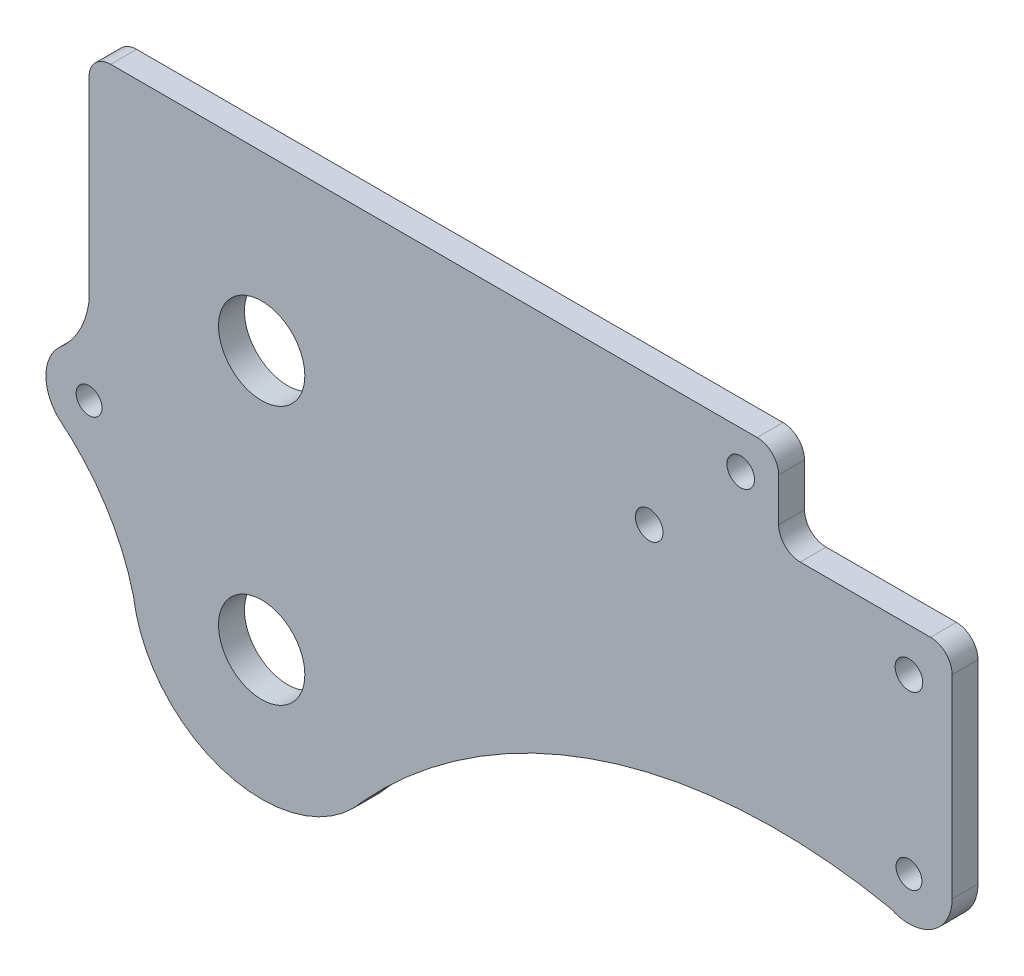
SolidWorks part; units mm, degrees
material "ｱｸﾘﾙ (中-上級の耐衝撃性)"
ref_plane "正面" through (0, 0, 0) normal (0, 0, 1) x (1, 0, 0)
ref_plane "平面" through (0, 0, 0) normal (0, 1, 0) x (1, 0, 0)
ref_plane "右側面" through (0, 0, 0) normal (1, 0, 0) x (0, 0, -1)
sketch "ｽｹｯﾁ1" plane through (0, 0, 0) normal (0, 0, 1) x (1, 0, 0)
  line L0 (0, 50) -> (100, 50) construction
  line L3 (0, 60) -> (100, 60)
  line L4 (100, 50) -> (100, 60)
  line L5 (10, 60) -> (50, 60)
  line L6 (10, 60) -> (10, 40)
  line L7 (10, 40) -> (50, 40)
  line L8 (50, 60) -> (50, 40)
  line L9 (30, 60) -> (30, 40) construction
  line L10 (100, 50) -> (100, 0)
  line L13 (0, 0) -> (100, 0)
  line L14 (0, 60) -> (0, 0)
  line L15 (20, 50) -> (20, 0) construction
  circle A0 centre (5.25, 55) radius 2.15
  circle A1 centre (5.25, 45) radius 2.15
  circle A2 centre (54.75, 55) radius 2.15
  circle A3 centre (54.75, 45) radius 2.15
  circle A4 centre (20, 20) radius 5
  dimension "D4" = 4.3
  dimension "D5" = 4.75
  dimension "D6" = 5
  dimension "D10" = 10
  dimension "D12" = 30
  dimension "D1" = 10
  dimension "D2" = 20
  dimension "D3" = 30
  dimension "D7" = 60
  dimension "D8" = 40
  dimension "D9" = 100
  dimension "D11" = 10
extrude "ﾎﾞｽ - 押し出し1" add sketch "ｽｹｯﾁ1" along normal blind 3
sketch "ｽｹｯﾁ2" plane through (0, 0, 3) normal (0, 0, 1) x (1, 0, 0)
  line L1 (100, 60) -> (100, 0) construction
  line L2 (50, 60) -> (100, 60) construction
  circle A1 centre (95, 35) radius 1.5
  dimension "D1" = 3
  dimension "D4" = 5
  dimension "D5" = 25
extrude "ｶｯﾄ - 押し出し1" cut sketch "ｽｹｯﾁ2" against normal through all
sketch "ｽｹｯﾁ4" plane through (0, 0, 3) normal (0, 0, 1) x (1, 0, 0)
  line L0 (0, 60) -> (0, 0) construction
  line L1 (5.25, 45) -> (1.5377, 41.2877) construction
  line L2 (5.25, 45) -> (5.25, 39.75) construction
  line L3 (20, 20) -> (6.1418, 25.7403) construction
  line L4 (5, 20) -> (20, 20) construction
  line L5 (20, 20) -> (30.6066, 9.3934) construction
  line L6 (95, 35) -> (95, 30) construction
  circle A0 centre (20, 20) radius 15
  circle A1 centre (95, 35) radius 5
  circle A2 centre (20, 20) radius 5 construction
  circle A3 centre (5.25, 45) radius 5.25
  arc A4 (1.5377, 41.2877) -> (6.1418, 25.7403) centre (-9.3863, 29.5973) cw
  arc A5 (30.6066, 9.3934) -> (95, 30) centre (79.7243, -33.1795) cw
  line M12 (0, 60) -> (0, 0)
  line M13 (0, 0) -> (100, 0)
  line M14 (100, 0) -> (100, 60)
  dimension "D1" = 10
  dimension "D2" = 10
  dimension "D5" = 16
  dimension "D6" = 135
  dimension "D7" = 65
  dimension "D3" = 45
  dimension "D4" = 22.5
extrude "ｶｯﾄ - 押し出し3" cut sketch "ｽｹｯﾁ4" against normal through all contours A5 A0 A4 A3 A1 M12 M13 M14
sketch "ｽｹｯﾁ5" plane through (0, 0, 3) normal (0, 0, 1) x (1, 0, 0)
  line L1 (10, 40) -> (100, 40)
  line L2 (10, 40) -> (10, 60)
  line L3 (10, 60) -> (100, 60)
  line L4 (100, 40) -> (100, 60)
  line L5 (10, 60) -> (3.1, 60)
  line L6 (10, 60) -> (10, 42.85)
  line L7 (10, 42.85) -> (3.1, 42.85)
  line L8 (3.1, 60) -> (3.1, 42.85)
  circle A0 centre (5.25, 45) radius 2.15 construction
  circle M5 centre (54.75, 45) radius 2.15
  circle M6 centre (5.25, 45) radius 2.15
  circle M7 centre (5.25, 55) radius 2.15
  circle M8 centre (54.75, 55) radius 2.15
  line M13 (50, 60) -> (50, 40)
  line M14 (50, 40) -> (10, 40)
  line M15 (10, 40) -> (10, 60)
  line M16 (10, 60) -> (0, 60)
extrude "ﾎﾞｽ - 押し出し2" add sketch "ｽｹｯﾁ5" against normal through all contours L8 L7 M6 | L8 L7 L2 M16 M7 M6 | M6 | M7 | L3 L2 M15 M14 M13 | M8 | M5
sketch "ｽｹｯﾁ6" plane through (0, 0, 3) normal (0, 0, 1) x (1, 0, 0)
  line L0 (20, 20) -> (20, 60) construction
  line L1 (0, 60) -> (100, 60) construction
  circle A0 centre (20, 50) radius 5
  dimension "D1" = 30
  dimension "D2" = 10
extrude "ｶｯﾄ - 押し出し4" cut sketch "ｽｹｯﾁ6" against normal through all
sketch "ｽｹｯﾁ7" plane through (0, 0, 3) normal (0, 0, 1) x (1, 0, 0)
  line L0 (0, 35) -> (-5, 35) construction
  line L1 (0, 35) -> (-3.5355, 38.5355) construction
  line L2 (0, 35) -> (-3.5355, 31.4645) construction
  circle A0 centre (0, 35) radius 5
  circle A1 centre (20, 50) radius 5 construction
  circle A2 centre (20, 20) radius 5 construction
  arc A3 (-3.5355, 38.5355) -> (0, 45) centre (-9.9242, 46.2287) ccw
  arc A4 (-3.5355, 31.4645) -> (5.1339, 18) centre (-19.1132, 11.9111) cw
  circle A6 centre (0, 35) radius 1.5
  arc A7 (6.1418, 25.7403) -> (31.7611, 10.69) centre (20, 20) ccw construction
  arc M8 (0, 45) -> (1.7318, 41.1032) centre (5.25, 45) ccw
  arc M9 (1.7318, 41.1032) -> (6.1418, 25.7403) centre (-9.3863, 29.5973) cw
  arc M10 (6.1418, 25.7403) -> (31.7611, 10.69) centre (20, 20) ccw
  dimension "D2" = 25
  dimension "D3" = 10
  dimension "D5" = 10
  dimension "D6" = 45
  dimension "D8" = 3
  dimension "D7" = 25
  dimension "D1" = 25
  dimension "D4" = 45
  dimension "D9" = 18
extrude "ﾎﾞｽ - 押し出し4" add sketch "ｽｹｯﾁ7" against normal through all contours A0 A4 A3 M10 M9 M8 | A0 A4 A3 A6
sketch "ｽｹｯﾁ8" plane through (0, 0, 3) normal (0, 0, 1) x (1, 0, 0)
  line L1 (95, 30.478) -> (95, 60) construction
  line L2 (0, 60) -> (100, 60) construction
  line L4 (100, 60) -> (100, 35) construction
  circle A0 centre (95, 45) radius 1.6
  circle A1 centre (95, 55) radius 1.6
  dimension "D1" = 3.2
  dimension "D2" = 5
  dimension "D3" = 10
  dimension "D4" = 5
sketch "ｽｹｯﾁ9" plane through (0, 0, 3) normal (0, 0, 1) x (1, 0, 0)
  line L0 (90, 60) -> (140, 110)
  line L1 (90, 39.1533) -> (100, 39.1533) construction
  line L2 (90, 39.1533) -> (90, 60)
  line L3 (90, 60) -> (100, 60)
  line L4 (100, 39.1533) -> (100, 60)
  line L5 (140, 110) -> (170, 110)
  line L6 (140, 110) -> (140, 100)
  line L7 (140, 100) -> (170, 100)
  line L8 (170, 110) -> (170, 100)
  line L9 (100, 60) -> (140, 100)
  line L10 (95, 60) -> (95, 39.1533) construction
  line L11 (115, 85) -> (120, 80) construction
  line L12 (140, 105) -> (170, 105) construction
  line L13 (90, 60) -> (90, 110)
  line L14 (90, 110) -> (140, 110)
  line L15 (110, 110) -> (90, 90)
  line L16 (90, 90) -> (60, 60)
  line L17 (60, 60) -> (90, 60)
  line L18 (70, 60) -> (120, 110)
  line L19 (60, 60) -> (70, 60)
  line L20 (60, 60) -> (60, 50)
  line L21 (60, 50) -> (70, 50)
  line L22 (70, 60) -> (70, 50)
  line L23 (64.9, 50) -> (64.9, 60) construction
  line L24 (96, 86) -> (96, 66)
  line L25 (134, 104) -> (114, 104)
  circle A0 centre (95, 35) radius 5
  circle A1 centre (95, 35) radius 6.5
  circle A2 centre (95, 55) radius 1.6
  circle A3 centre (95, 45) radius 1.6
  circle A4 centre (150, 105) radius 1.3
  circle A5 centre (160, 105) radius 1.3
  circle A6 centre (64.9, 55) radius 1.6
  circle A9 centre (95, 35) radius 1.5
  dimension "D1" = 10
  dimension "D2" = 13
  dimension "D8" = 3.2
  dimension "D11" = 2.6
  dimension "D17" = 3.2
  dimension "D20" = 3
  dimension "D3" = 25
  dimension "D4" = 30
  dimension "D5" = 10
  dimension "D6" = 40
  dimension "D7" = 40
  dimension "D9" = 5
  dimension "D10" = 15
  dimension "D12" = 10
  dimension "D13" = 20
  dimension "D14" = 45
  dimension "D15" = 20
  dimension "D16" = 10
  dimension "D18" = 6
  dimension "D19" = 6
  dimension "D21" = 5.1
extrude "ｶｯﾄ - 押し出し6" cut sketch "ｽｹｯﾁ9" against normal through all and the other way through all contours A6
extrude "ｶｯﾄ - 押し出し7" cut sketch "ｽｹｯﾁ8" against normal through all contours L1 A1 | A1 L1
sketch "ｽｹｯﾁ10" plane through (0, 0, 3) normal (0, 0, 1) x (1, 0, 0)
  line L0 (64.9, 55) -> (79.9, 70) construction
  line L1 (0, 60) -> (79.9, 60)
  line L2 (0, 60) -> (0, 70)
  line L3 (0, 70) -> (79.9, 70)
  line L4 (79.9, 60) -> (79.9, 70)
  circle A0 centre (75.5066, 65.6066) radius 1.6
  circle A1 centre (64.9, 55) radius 1.6 construction
  dimension "D4" = 15
  dimension "D1" = 10
  dimension "D3" = 45
extrude "ﾎﾞｽ - 押し出し5" add sketch "ｽｹｯﾁ10" against normal through all
fillet "ﾌｨﾚｯﾄ1" radius 2.5 4 edges at (0, 70, 1.5) (100, 60, 1.5) (79.9, 60, 1.5) (79.9, 70, 1.5)
